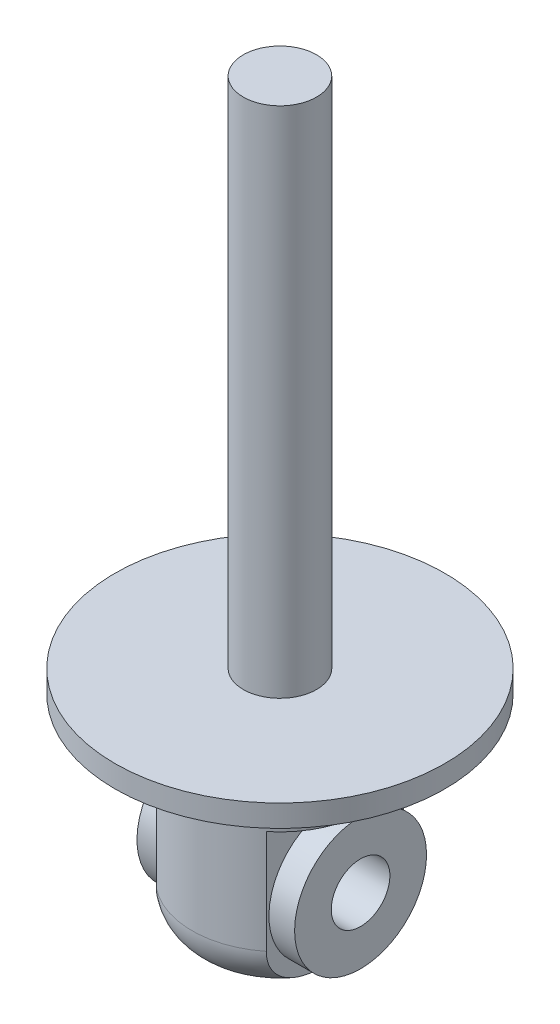
SolidWorks part; units mm, degrees
ref_plane "Front Plane" through (0, 0, 0) normal (0, 0, 1) x (1, 0, 0)
ref_plane "Top Plane" through (0, 0, 0) normal (0, 1, 0) x (1, 0, 0)
ref_plane "Right Plane" through (0, 0, 0) normal (1, 0, 0) x (0, 0, -1)
sketch "Sketch1" plane through (0, 0, 0) normal (0, 1, 0) x (1, 0, 0)
  circle A0 centre (0, 0) radius 22.5
  dimension "D1" = 45
extrude "Boss-Extrude1" add sketch "Sketch1" along normal blind 3
sketch "Sketch2" plane through (0, 3, 0) normal (0, 1, 0) x (1, 0, 0)
  circle A0 centre (0, 0) radius 5
  dimension "D1" = 10
extrude "Boss-Extrude2" add sketch "Sketch2" along normal blind 70
sketch "Sketch3" plane through (0, 0, 0) normal (0, -1, 0) x (1, 0, 0)
  circle A0 centre (0, 0) radius 12
  dimension "D1" = 24
extrude "Boss-Extrude3" add sketch "Sketch3" along normal blind 28
fillet "Fillet1" radius 6 1 edges at (0, -28, -12)
sketch "Sketch4" plane through (0, 0, 0) normal (0, 0, 1) x (1, 0, 0)
  line L0 (0, 0) -> (0, -27.8409) construction
  line L1 (-23.4977, -27.8409) -> (23.4977, -27.8409)
  line L2 (23.4977, -27.8409) -> (23.4977, -7.8409)
  line L3 (23.4977, -7.8409) -> (7.5, -7.8409)
  line L4 (7.5, -7.8409) -> (7.5, -27.8409)
  line L5 (-7.5, -7.8409) -> (-7.5, -27.8409)
  line L6 (-23.4977, -7.8409) -> (-7.5, -7.8409)
  line L7 (-23.4977, -27.8409) -> (-23.4977, -7.8409)
  dimension "D1" = 15
  dimension "D2" = 20
extrude "Cut-Extrude1" cut sketch "Sketch4" against normal through all both and the other way through all contours L7 L1 L5 L6 | L3 L4 L1 L2
sketch "Sketch5" plane through (7.5, 0, 0) normal (1, 0, 0) x (0, 0, -1)
  line L0 (0, 0) -> (0, -28) construction
  line L1 (-6, -28) -> (6, -28) construction
  circle A0 centre (0, -18) radius 4
  dimension "D1" = 8
  dimension "D2" = 10
extrude "Cut-Extrude2" cut sketch "Sketch5" against normal through all
sketch "Sketch6" plane through (7.5, 0, 0) normal (1, 0, 0) x (0, 0, -1)
  circle A0 centre (0, -18) radius 9
  circle A1 centre (0, -18) radius 4 construction
  circle A2 centre (0, -18) radius 4
  dimension "D1" = 18
extrude "Boss-Extrude15" add sketch "Sketch6" along normal mid plane 7
sketch "Sketch10" plane through (-7.5, 0, 0) normal (-1, 0, 0) x (0, 0, 1)
  circle A0 centre (0, -18) radius 9
  circle A1 centre (0, -18) radius 4 construction
  circle A2 centre (0, -18) radius 4
  dimension "D1" = 18
extrude "Boss-Extrude19" add sketch "Sketch10" along normal blind 3
